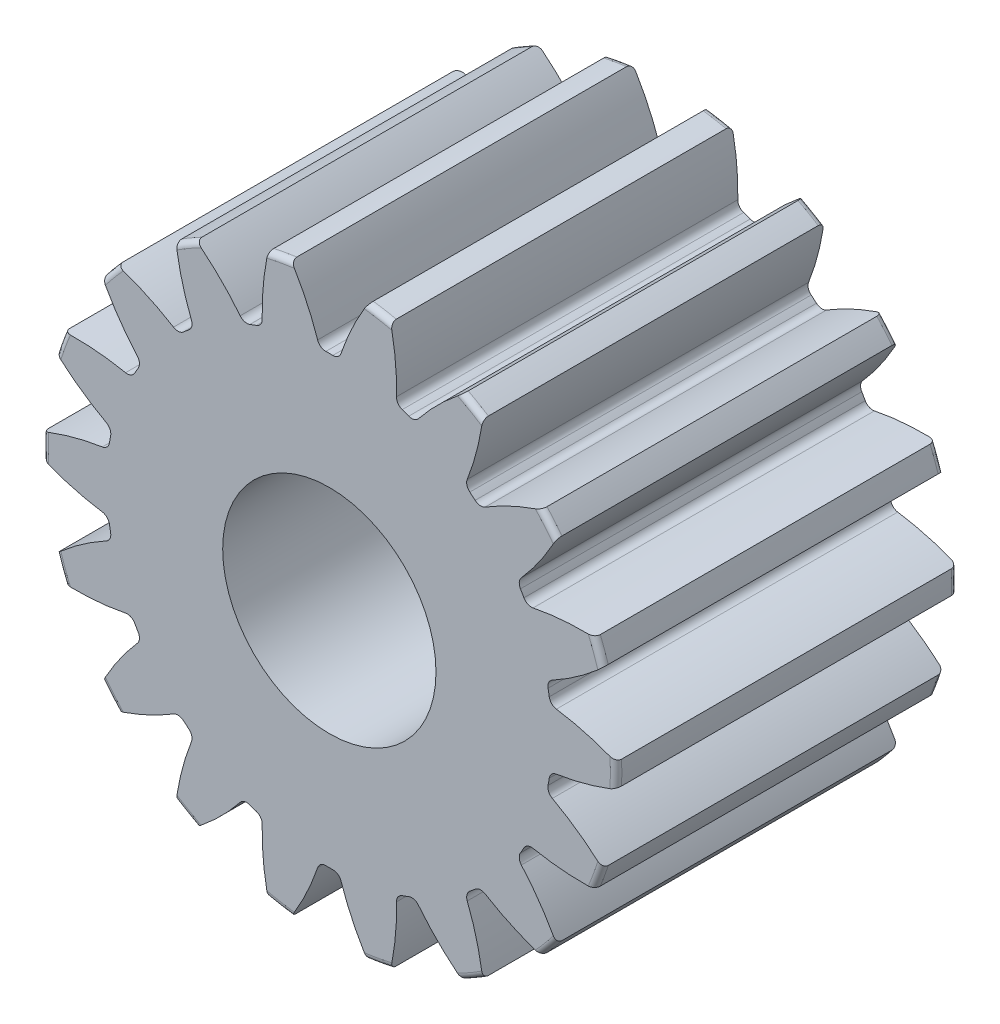
SolidWorks part; units mm, degrees
ref_plane "Front Plane" through (0, 0, 0) normal (0, 0, 1) x (1, 0, 0)
ref_plane "Top Plane" through (0, 0, 0) normal (0, 1, 0) x (1, 0, 0)
ref_plane "Right Plane" through (0, 0, 0) normal (1, 0, 0) x (0, 0, -1)
sketch "Sketch1" plane through (0, 0, 0) normal (0, 0, 1) x (1, 0, 0)
  line L0 (-228.6, 0) -> (228.6, 0) construction
  circle A0 centre (0, 0) radius 5.334 construction
  circle A1 centre (0, 0) radius 4.7625 construction
  circle A2 centre (0, 0) radius 4.1434 construction
  circle A3 centre (0, 0) radius 3.9751 construction
  circle A4 centre (0, 0) radius 1.9844 construction
  dimension "D2" = 0.5715
  dimension "D3" = 1.1906
  dimension "D1" = 1.1906
sketch "Sketch2" plane through (0, 0, 0) normal (1, 0, 0) x (0, 0, -1)
  line L0 (0, 0) -> (-3.175, 0) construction
  line L1 (-3.175, 0) -> (-9.525, 0) construction
  dimension "Overall Width" = 9.525
  dimension "Face Width" = 3.175
sketch "Sketch4" plane through (0, 0, 0) normal (1, 0, 0) x (0, 0, -1)
  line L0 (-9.525, 1.9844) -> (-9.525, 3.9751)
  line L1 (-9.525, 3.9751) -> (-6.35, 3.9751)
  line L2 (-6.35, 3.9751) -> (-6.35, 5.334)
  line L3 (-6.35, 5.334) -> (0, 5.334)
  line L4 (0, 5.334) -> (0, 1.9844)
  line L5 (-6.35, 3.9751) -> (-6.35, 0) construction
  line L6 (0, 5.334) -> (0, -5.334) construction
  line L7 (-6.35, 3.9751) -> (0, 3.9751) construction
  line L12 (-9.525, 1.9844) -> (0, 1.9844)
  point P2 (-6.35, -2.6539)
  point P8 (-6.35, 0)
  point P10 (-6.35, -0.2486)
  dimension "D1" = 6.35
  dimension "D2" = 1.9844
revolve "Revolve1" add sketch "Sketch4" angle 360 about L1
fillet "Fillet2" radius 0.1067 4 edges at (0, 3.9751, 9.525) (0, 3.9751, 6.35) (0, 5.334, 6.35) (0, 5.334, 0)
sketch "Sketch7" plane through (0, 0, 6.35) normal (0, 0, 1) x (1, 0, 0)
  line L0 (0, 0) -> (0, 5.334) construction
  line L1 (0.4151, 4.7444) -> (0.6703, 5.2917) construction
  line L3 (0.9262, 5.253) -> (0.827, 4.6901) construction
  line L4 (0.827, 4.6901) -> (0.7195, 4.0804) construction
  line L5 (0, 0) -> (0.7195, 4.0804) construction
  line L6 (0.4151, 4.7444) -> (0, 0) construction
  line L7 (0.4151, 4.7444) -> (0.4649, 5.3137) construction
  line L8 (0.4151, 4.7444) -> (0, 0) construction
  circle A0 centre (0, 0) radius 5.334 construction
  arc A1 (-0.0648, 4.1429) -> (0.0648, 4.1429) centre (0, 0) cw
  circle A2 centre (0, 0) radius 4.1434 construction
  arc A3 (-0.4151, 4.7444) -> (0.4151, 4.7444) centre (0, 0) cw construction
  circle A4 centre (0, 0) radius 4.7625 construction
  arc A5 (1.139, 5.211) -> (0.712, 5.2863) centre (0, 0) ccw construction
  arc A6 (0.4151, 4.7444) -> (1.2326, 4.6002) centre (0, 0) cw construction
  arc A7 (-0.712, 5.2863) -> (0.712, 5.2863) centre (0, 0) cw
  arc A8 (0.2177, 4.251) -> (0.712, 5.2863) centre (4.7314, 2.7317) cw
  arc A9 (-0.2177, 4.251) -> (-0.712, 5.2863) centre (-4.7314, 2.7317) ccw
  arc A10 (-0.0648, 4.1429) -> (-0.2177, 4.251) centre (-0.0672, 4.3016) cw
  arc A11 (0.0648, 4.1429) -> (0.2177, 4.251) centre (0.0672, 4.3016) ccw
  point P26 (-0.1817, 4.1394)
  point P29 (0.1817, 4.1394)
  dimension "D4" = 0.1588
  dimension "D5" = 4.7625
  dimension "D3" = 20
  dimension "D1" = 1.6624
  dimension "D2" = 0.8312
extrude "Cut-Extrude2" cut sketch "Sketch7" against normal through all
pattern_circular "CirPattern1" count 18 over 360 about axis through (0, 0, 0) along (0, 0, 1) of "Cut-Extrude2"
sketch "Sketch8" plane through (0, 0, 0) normal (0, 1, 0) x (1, 0, 0)
  line L0 (-3.8684, -9.525) -> (3.8684, -9.525) construction
  line L1 (-4.0818, -6.35) -> (4.0818, -6.35)
  line L2 (-4.0818, -6.35) -> (-4.0818, -9.525)
  line L3 (-4.0818, -9.525) -> (4.0818, -9.525)
  line L4 (4.0818, -6.35) -> (4.0818, -9.525)
  line L5 (-4.0818, -6.35) -> (4.0818, -6.35) construction
  point P4 (0, -9.525)
extrude "Cut-Extrude3" cut sketch "Sketch8" against normal through all both and the other way through all
sketch "Sketch9" plane through (0, 0, 0) normal (0, 0, 1) x (1, 0, 0)
  circle A0 centre (0, 0) radius 4.7625
  circle A1 centre (0, 0) radius 4.7625 construction
equation "\"D1@Sketch1\"=2.25*(\"Pitch Dia.@Sketch1\"/\"Number of Teeth@Sketch1\")"
equation "\"D1@CirPattern1\"=\"Number of Teeth@Sketch1\""
equation "\"D1@Fillet2\"=\"OD@Sketch1\"*.01"
equation "\"D1@Sketch7\"=3.14159*(\"Pitch Dia.@Sketch1\"/\"Number of Teeth@Sketch1\")"
equation "\"D2@Sketch7\"=\"D1@Sketch7\"/2"
equation "\"D4@Sketch7\"=\"D1@Sketch7\"*.0955"
equation "\"D5@Sketch7\"=\"Pitch Dia.@Sketch1\"/2"
